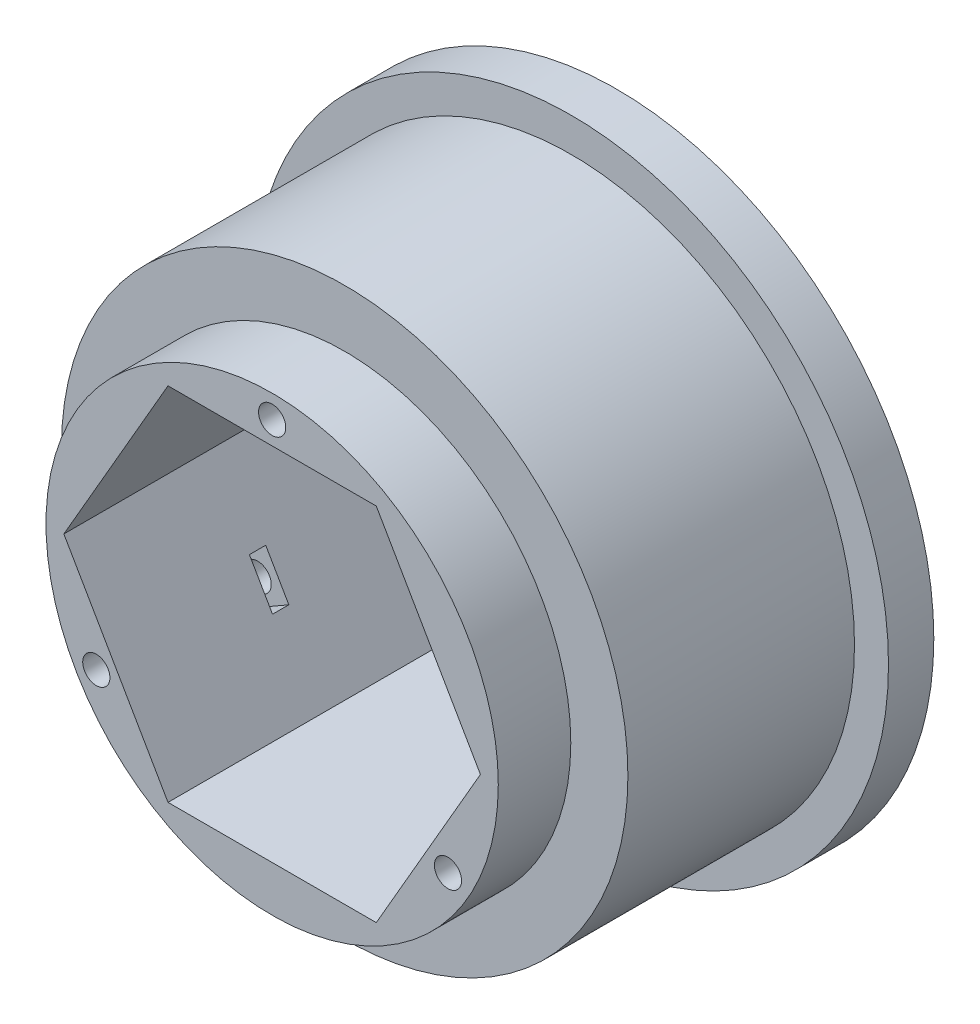
SolidWorks part; units mm, degrees
ref_plane "Front Plane" through (0, 0, 0) normal (0, 0, 1) x (1, 0, 0)
ref_plane "Top Plane" through (0, 0, 0) normal (0, 1, 0) x (1, 0, 0)
ref_plane "Right Plane" through (0, 0, 0) normal (1, 0, 0) x (0, 0, -1)
sketch "Sketch1" plane through (0, 0, 0) normal (0, 1, 0) x (1, 0, 0)
  line L0 (0, -57.8258) -> (0, 28.2892) construction
  line L1 (-52.6765, 0) -> (55.0176, 0) construction
  line L2 (19.9, -38) -> (19.9, -5)
  line L3 (19.9, -5) -> (24.95, -5)
  line L4 (24.95, -5) -> (24.95, -10)
  line L5 (24.95, -10) -> (28.1, -10)
  line L6 (28.1, -10) -> (28.1, 0)
  line L7 (28.1, 0) -> (42, 0)
  line L8 (42, 0) -> (42, -5)
  line L9 (42, -5) -> (31.25, -5)
  line L10 (31.25, -5) -> (31.25, -30)
  line L11 (31.25, -30) -> (24.95, -30)
  line L12 (24.95, -30) -> (24.95, -38)
  line L13 (24.95, -38) -> (19.9, -38)
  dimension "D1" = 19.9
  dimension "D2" = 31.25
  dimension "D3" = 5.05
  dimension "D4" = 20
  dimension "D5" = 5
  dimension "D6" = 3.15
  dimension "D7" = 5
  dimension "D8" = 42
  dimension "D9" = 8
  dimension "D10" = 28.1
  dimension "D11" = 25
revolve "Revolve1" add sketch "Sketch1" angle 360 about L0
sketch "Sketch2" plane through (0, 0, 38) normal (0, 0, 1) x (1, 0, 0)
  line L0 (0, 62.8833) -> (0, -55.5421) construction
  line L1 (-81.1397, 0) -> (57.3774, 0) construction
  line L3 (-22.9785, 0) -> (-11.4893, -19.9)
  line L4 (-11.4893, -19.9) -> (11.4893, -19.9)
  line L5 (11.4893, -19.9) -> (22.9785, 0)
  line L6 (22.9785, 0) -> (11.4893, 19.9)
  line L7 (11.4893, 19.9) -> (-11.4893, 19.9)
  line L8 (-11.4893, 19.9) -> (-22.9785, 0)
  circle A0 centre (0, 0) radius 19.9 construction
  dimension "D1" = 39.8
extrude "Cut-Extrude1" cut sketch "Sketch2" against normal through all
sketch "Sketch3" plane through (0, 0, 38) normal (0, 0, 1) x (1, 0, 0)
  line L0 (-63.7526, 0) -> (72.9292, 0) construction
  line L1 (0, 56.1055) -> (0, -55.4616) construction
  circle A0 centre (0, 22.4) radius 1.5
  circle A1 centre (19.399, -11.2) radius 1.5
  circle A2 centre (-19.399, -11.2) radius 1.5
  point P13 (0, 0)
  dimension "D1" = 3
  dimension "D2" = 22.4
  dimension "D3" = 3
extrude "Cut-Extrude2" cut sketch "Sketch3" against normal blind 20
ref_plane "Plane1" through (0, 0, 22) normal (0, 0, 1) x (1, 0, 0)
sketch "Sketch4" plane through (0, 0, 22) normal (0, 0, 1) x (1, 0, 0)
  line L0 (0, 46.4212) -> (0, -45.1414) construction
  line L1 (-64.0152, 0) -> (51.3086, 0) construction
  line L7 (-2.55, 24.95) -> (2.55, 24.95)
  line L8 (2.55, 24.95) -> (2.55, 19.9)
  line L10 (-2.55, 19.9) -> (-2.55, 24.95)
  line L11 (11.4893, 19.9) -> (-11.4893, 19.9) construction
  line L12 (-2.55, 19.9) -> (2.55, 19.9)
  line L13 (18.5089, -7.7416) -> (15.9589, -12.1584)
  line L14 (20.3323, -14.6834) -> (15.9589, -12.1584)
  line L15 (22.8823, -10.2666) -> (20.3323, -14.6834)
  line L16 (18.5089, -7.7416) -> (22.8823, -10.2666)
  line L17 (-15.9589, -12.1584) -> (-18.5089, -7.7416)
  line L18 (-22.8823, -10.2666) -> (-18.5089, -7.7416)
  line L19 (-20.3323, -14.6834) -> (-22.8823, -10.2666)
  line L20 (-15.9589, -12.1584) -> (-20.3323, -14.6834)
  circle A6 centre (0, 22.4) radius 1.5 construction
  point P26 (0, 0)
  dimension "D1" = 5.1
  dimension "D2" = 2.55
  dimension "D3" = 3
  dimension "D4" = 2.55
extrude "Cut-Extrude3" cut sketch "Sketch4" against normal blind 1.8
sketch "Sketch5" plane through (0, 0, 0) normal (0, 1, 0) x (1, 0, 0)
  line L0 (0, 13.7075) -> (0, -47.4571) construction
sketch "Sketch6" plane through (0, 0, 0) normal (0, 0, -1) x (-1, 0, 0)
  line L0 (0, 50.3769) -> (0, -43.4006) construction
  circle A0 centre (0, 38) radius 2.55
  circle A1 centre (38, 0) radius 2.55
  circle A2 centre (0, -38) radius 2.55
  circle A3 centre (-38, 0) radius 2.55
  point P14 (0, 0)
  dimension "D1" = 5.1
  dimension "D2" = 38
  dimension "D3" = 4
extrude "Cut-Extrude4" cut sketch "Sketch6" against normal blind 3
sketch "Sketch7" plane through (0, 0, 3) normal (0, 0, -1) x (-1, 0, 0)
  circle A0 centre (0, 38) radius 1.75
  circle A1 centre (38, 0) radius 1.75
  circle A2 centre (0, -38) radius 1.75
  circle A3 centre (-38, 0) radius 1.75
  point P12 (0, 0)
  dimension "D1" = 3.5
  dimension "D2" = 4
extrude "Cut-Extrude5" cut sketch "Sketch7" against normal blind 3
sketch "Sketch8" plane through (0, 0, 0) normal (0, 0, 1) x (1, 0, 0)
  circle A0 centre (0, 0) radius 35
  dimension "D1" = 70
extrude "Cut-Extrude6" cut sketch "Sketch8" along normal through all flip side to cut
